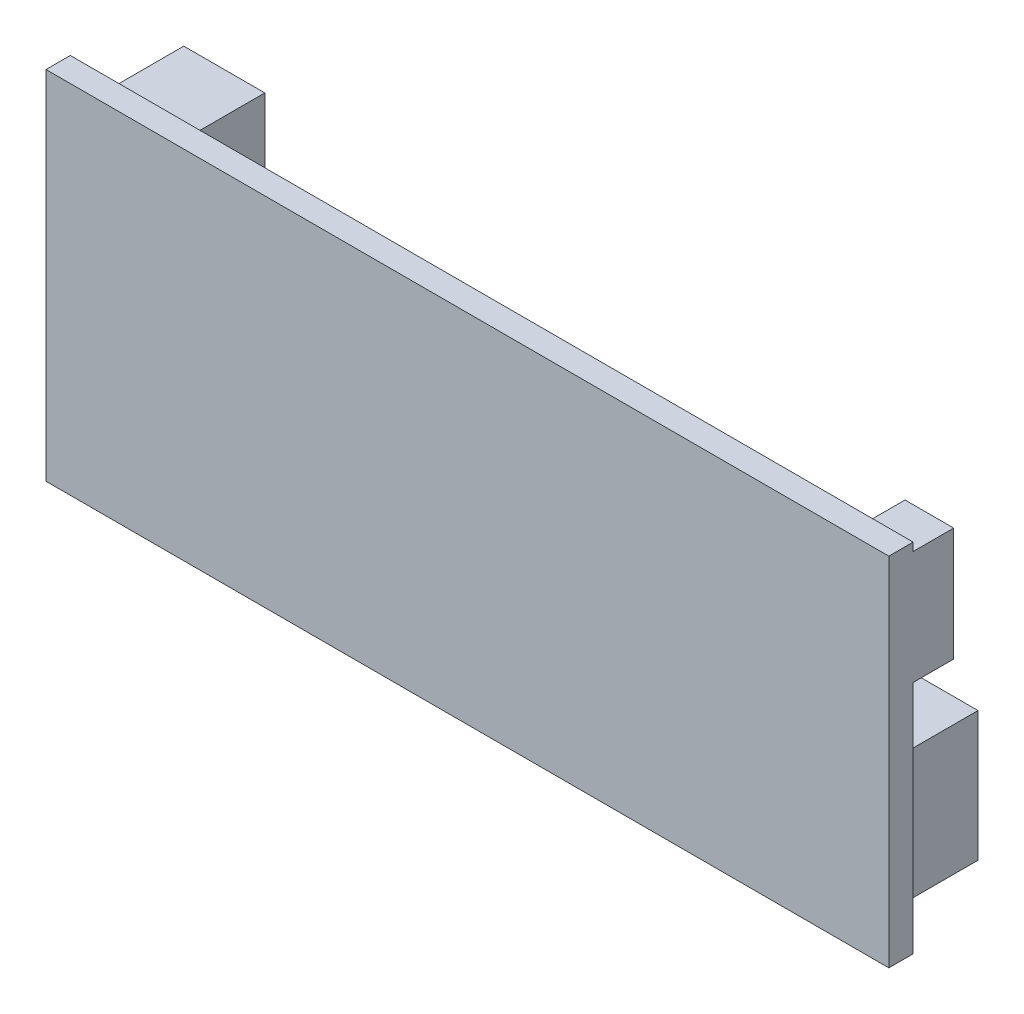
SolidWorks part; units mm, degrees
ref_plane "Front Plane" through (0, 0, 0) normal (0, 0, 1) x (1, 0, 0)
ref_plane "Top Plane" through (0, 0, 0) normal (0, 1, 0) x (1, 0, 0)
ref_plane "Right Plane" through (0, 0, 0) normal (1, 0, 0) x (0, 0, -1)
sketch "Sketch1" plane through (0, 0, 0) normal (0, 0, 1) x (1, 0, 0)
  line L0 (-19.2815, 22) -> (-19.2815, 0)
  line L1 (-19.2815, 0) -> (32.7185, 0)
  line L2 (32.7185, 0) -> (32.7185, 22)
  line L3 (32.7185, 22) -> (-19.2815, 22)
extrude "Boss-Extrude1" add sketch "Sketch1" along normal blind 1.5
sketch "Sketch2" plane through (0, 0, 0) normal (0, 0, -1) x (-1, 0, 0)
  line L0 (-32.7185, 0) -> (-32.7185, 22) construction
  line L1 (17.7815, 20.5) -> (12.7815, 20.5)
  line L2 (17.7815, 20.5) -> (17.7815, 15.5)
  line L3 (17.7815, 15.5) -> (12.7815, 15.5)
  line L4 (12.7815, 20.5) -> (12.7815, 15.5)
  line L5 (-31.2185, 1.5) -> (-21.2185, 1.5)
  line L6 (-31.2185, 1.5) -> (-31.2185, 9.5)
  line L7 (-31.2185, 9.5) -> (-21.2185, 9.5)
  line L8 (-21.2185, 1.5) -> (-21.2185, 9.5)
  line L9 (-32.7185, 21.5) -> (-29.7185, 21.5)
  line L10 (-32.7185, 21.5) -> (-32.7185, 14.5)
  line L11 (-32.7185, 14.5) -> (-29.7185, 14.5)
  line L12 (-29.7185, 21.5) -> (-29.7185, 14.5)
  line L13 (-28.7185, 21.5) -> (-32.7185, 21.5) construction
  line L14 (-28.7185, 14.5) -> (-32.7185, 14.5) construction
  line L15 (19.2815, 22) -> (19.2815, 0) construction
  line L16 (17.7815, 7.9) -> (19.2815, 7.9)
  line L17 (17.7815, 7.9) -> (17.7815, 3.0979)
  line L18 (17.7815, 3.0979) -> (19.2815, 3.0979)
  line L19 (19.2815, 7.9) -> (19.2815, 3.0979)
  line L20 (32.1478, 3.0979) -> (17.1478, 3.0979) construction
  dimension "D1" = 5
  dimension "D2" = 5
  dimension "D3" = 10
  dimension "D4" = 8
  dimension "D5" = 3
extrude "Boss-Extrude2" add sketch "Sketch2" along normal blind 2.5
sketch "Sketch3" plane through (0, 0, -2.5) normal (0, 0, -1) x (-1, 0, 0)
  line L0 (-31.2185, 9.5) -> (-31.2185, 1.5) construction
  line L1 (-31.2185, 1.5) -> (-21.2185, 1.5) construction
  line L2 (-21.2185, 1.5) -> (-21.2185, 9.5) construction
  line L3 (-21.2185, 9.5) -> (-31.2185, 9.5) construction
  line L4 (17.7815, 7.9) -> (17.7815, 3.0979) construction
  line L5 (17.7815, 3.0979) -> (19.2815, 3.0979) construction
  line L6 (19.2815, 3.0979) -> (19.2815, 7.9) construction
  line L7 (19.2815, 7.9) -> (17.7815, 7.9) construction
  line L8 (17.7815, 15.5) -> (17.7815, 20.5) construction
  line L9 (17.7815, 20.5) -> (12.7815, 20.5) construction
  line L10 (12.7815, 20.5) -> (12.7815, 15.5) construction
  line L11 (12.7815, 15.5) -> (17.7815, 15.5) construction
  line L12 (-31.2185, 9.5) -> (-31.2185, 1.5)
  line L13 (-31.2185, 1.5) -> (-21.2185, 1.5)
  line L14 (-21.2185, 1.5) -> (-21.2185, 9.5)
  line L15 (-21.2185, 9.5) -> (-31.2185, 9.5)
  line L16 (17.7815, 7.9) -> (17.7815, 3.0979)
  line L17 (17.7815, 3.0979) -> (19.2815, 3.0979)
  line L18 (19.2815, 3.0979) -> (19.2815, 7.9)
  line L19 (19.2815, 7.9) -> (17.7815, 7.9)
  line L20 (17.7815, 15.5) -> (17.7815, 20.5)
  line L21 (17.7815, 20.5) -> (12.7815, 20.5)
  line L22 (12.7815, 20.5) -> (12.7815, 15.5)
  line L23 (12.7815, 15.5) -> (17.7815, 15.5)
extrude "Boss-Extrude3" add sketch "Sketch3" along normal blind 3
